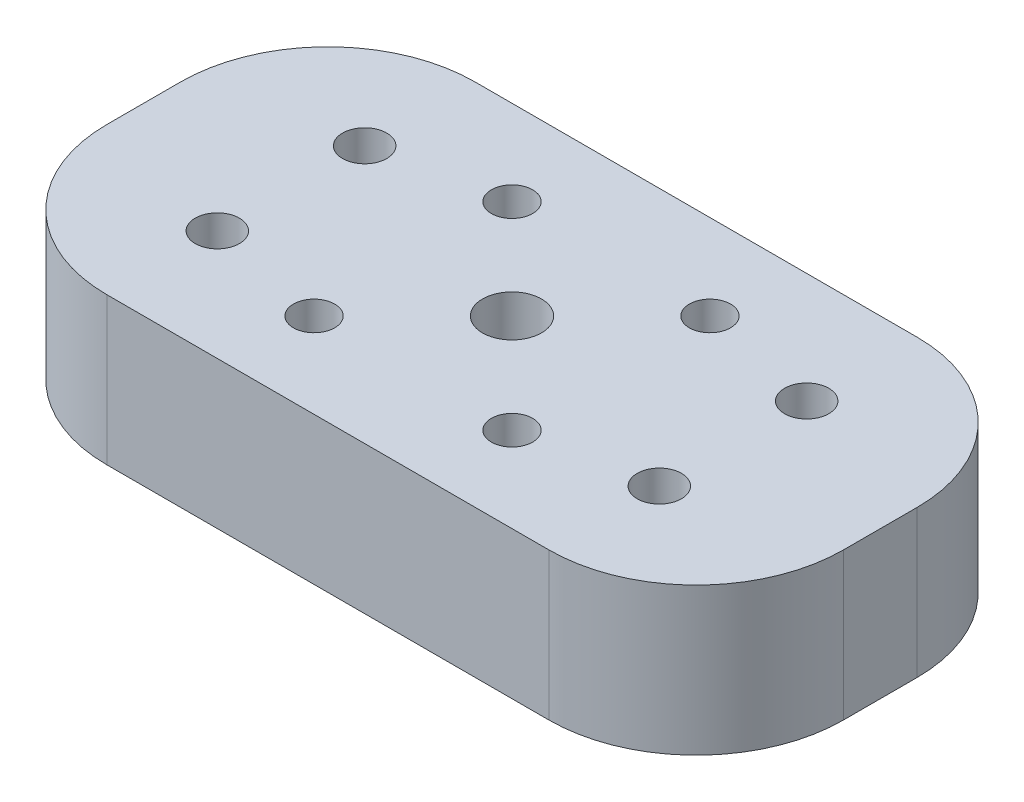
SolidWorks part; units mm, degrees
ref_plane "Front Plane" through (0, 0, 0) normal (0, 0, 1) x (1, 0, 0)
ref_plane "Top Plane" through (0, 0, 0) normal (0, 1, 0) x (1, 0, 0)
ref_plane "Right Plane" through (0, 0, 0) normal (1, 0, 0) x (0, 0, -1)
sketch "Sketch1" plane through (0, 0, 0) normal (0, 1, 0) x (1, 0, 0)
  line L1 (25, 12.5) -> (-25, 12.5)
  line L2 (25, 12.5) -> (25, -12.5)
  line L3 (25, -12.5) -> (-25, -12.5)
  line L4 (-25, 12.5) -> (-25, -12.5)
  line L5 (25, 12.5) -> (-25, -12.5) construction
  line L6 (25, -12.5) -> (-25, 12.5) construction
  point P0 (0, 0)
  dimension "D1" = 50
  dimension "D2" = 25
extrude "Boss-Extrude1" add sketch "Sketch1" along normal blind 10
sketch "Sketch2" plane through (0, 10, 0) normal (0, 1, 0) x (1, 0, 0)
  line L0 (0, -55) -> (0, 55) construction
  circle A0 centre (-15, 5) radius 1.5
  circle A1 centre (-15, -5) radius 1.5
  circle A2 centre (15, -5) radius 1.5
  circle A3 centre (15, 5) radius 1.5
  dimension "D4" = 3
  dimension "D5" = 3
  dimension "D2" = 10
  dimension "D3" = 15
  dimension "D6" = 5
extrude "Cut-Extrude1" cut sketch "Sketch2" against normal blind 10
sketch "Sketch3" plane through (0, 10, 0) normal (0, 1, 0) x (1, 0, 0)
  circle A0 centre (0, 0) radius 9.5 construction
  circle A1 centre (-6.7175, -6.7175) radius 1.4
  circle A2 centre (6.7175, -6.7175) radius 1.4
  circle A3 centre (6.7175, 6.7175) radius 1.4
  circle A4 centre (-6.7175, 6.7175) radius 1.4
  dimension "D1" = 19
  dimension "D2" = 2.8
  dimension "D3" = 2.8
  dimension "D4" = 2.8
  dimension "D5" = 2.8
extrude "Cut-Extrude2" cut sketch "Sketch3" against normal blind 10
sketch "Sketch4" plane through (0, 10, 0) normal (0, 1, 0) x (1, 0, 0)
  circle A0 centre (0, 0) radius 2
  dimension "D1" = 4
extrude "Cut-Extrude3" cut sketch "Sketch4" against normal blind 10
fillet "Fillet1" radius 10 4 edges at (25, 5, 12.5) (-25, 5, 12.5) (-25, 5, -12.5) (25, 5, -12.5)
sketch "Sketch5" plane through (0, 0, 0) normal (0, -1, 0) x (1, 0, 0)
  circle A0 centre (-6.7175, 6.7175) radius 3.5
  circle A1 centre (6.7175, 6.7175) radius 3.5
  circle A2 centre (6.7175, -6.7175) radius 3.5
  circle A3 centre (-6.7175, -6.7175) radius 3.5
  dimension "D1" = 7
  dimension "D2" = 7
  dimension "D3" = 7
  dimension "D4" = 7
extrude "Cut-Extrude4" cut sketch "Sketch5" against normal blind 4
